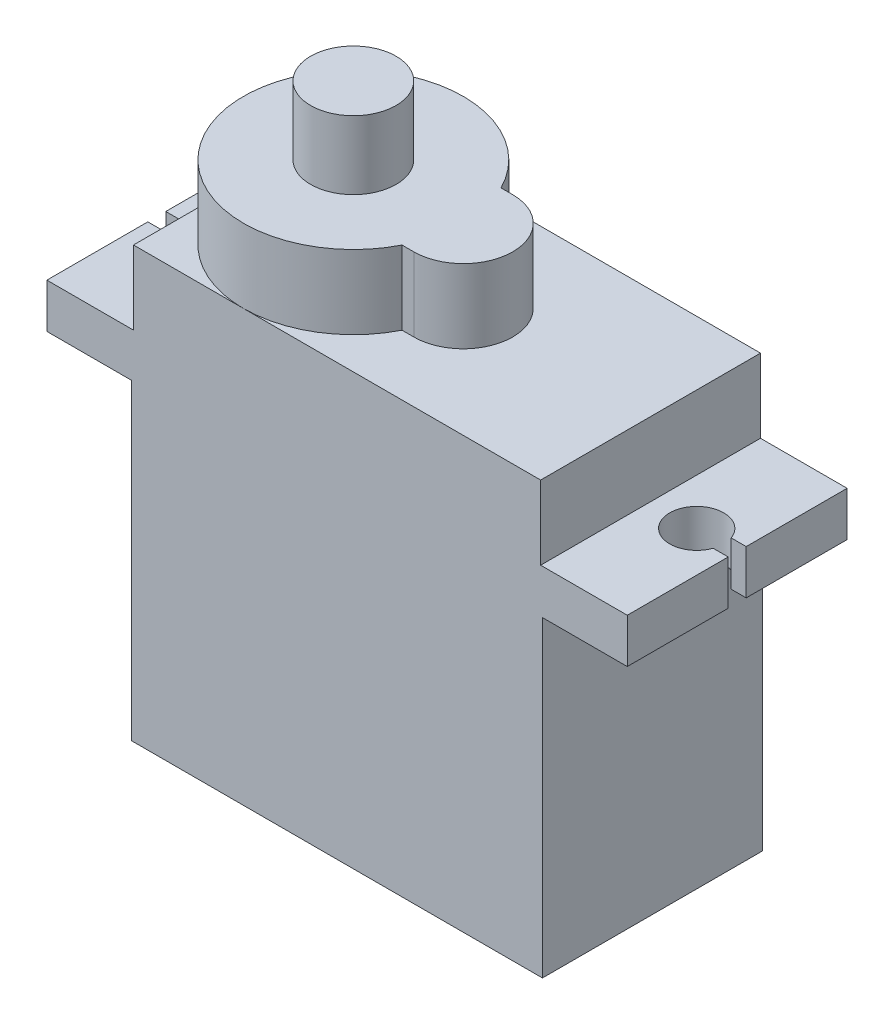
SolidWorks part; units mm, degrees
ref_plane "Front Plane" through (0, 0, 0) normal (0, 0, 1) x (1, 0, 0)
ref_plane "Top Plane" through (0, 0, 0) normal (0, 1, 0) x (1, 0, 0)
ref_plane "Right Plane" through (0, 0, 0) normal (1, 0, 0) x (0, 0, -1)
sketch "Sketch1" plane through (0, 0, 0) normal (0, 1, 0) x (1, 0, 0)
  line L1 (0, 0) -> (22.83, 0)
  line L2 (0, 0) -> (0, 12.22)
  line L3 (0, 12.22) -> (22.83, 12.22)
  line L4 (22.83, 0) -> (22.83, 12.22)
  dimension "D1" = 22.83
  dimension "D2" = 12.22
extrude "Boss-Extrude1" add sketch "Sketch1" along normal blind 17.35
sketch "Sketch2" plane through (0, 17.35, 0) normal (0, 1, 0) x (1, 0, 0)
  line L0 (22.83, 12.22) -> (0, 12.22) construction
  line L1 (-4.715, 0) -> (27.545, 0)
  line L2 (-4.715, 0) -> (-4.715, 12.22) construction
  line L3 (-4.715, 12.22) -> (27.545, 12.22)
  line L5 (0, 0) -> (22.83, 0) construction
  line L6 (11.415, 0) -> (11.415, 12.22) construction
  line L7 (-4.715, 5.61) -> (-3.8792, 5.61)
  line L8 (-2.465, 6.11) -> (-4.715, 6.11) construction
  line L9 (-2.465, 6.11) -> (-0.965, 6.11) construction
  line L10 (-4.715, 6.61) -> (-3.8792, 6.61)
  line L11 (-4.715, 0) -> (-4.715, 5.61)
  line L12 (-4.715, 6.61) -> (-4.715, 12.22)
  line L13 (25.295, 6.11) -> (23.795, 6.11) construction
  line L14 (25.295, 6.11) -> (27.545, 6.11) construction
  line L15 (27.545, 0) -> (27.545, 12.22) construction
  line L16 (27.545, 6.61) -> (27.545, 12.22)
  line L17 (27.545, 0) -> (27.545, 5.61)
  line L18 (27.545, 6.61) -> (26.7092, 6.61)
  line L19 (27.545, 5.61) -> (26.7092, 5.61)
  arc A0 (-3.8792, 5.61) -> (-3.8792, 6.61) centre (-2.465, 6.11) ccw
  arc A1 (26.7092, 5.61) -> (26.7092, 6.61) centre (25.295, 6.11) cw
  point P17 (-1.8734, 6.11)
  point P18 (0, 0)
  dimension "D2" = 1.5
  dimension "D1" = 32.26
  dimension "D3" = 0.5
  dimension "D4" = 3.75
extrude "Boss-Extrude2" add sketch "Sketch2" along normal blind 2.47
sketch "Sketch3" plane through (0, 19.82, 0) normal (0, 1, 0) x (1, 0, 0)
  line L0 (11.415, 0) -> (11.415, 12.22) construction
  line L1 (0.1, 12.22) -> (22.73, 12.22)
  line L2 (0.1, 12.22) -> (0.1, 0)
  line L3 (0.1, 0) -> (22.73, 0)
  line L4 (22.73, 12.22) -> (22.73, 0)
  line L5 (-4.715, 0) -> (27.545, 0) construction
  line L6 (27.545, 12.22) -> (-4.715, 12.22) construction
  point P4 (0, 0)
  dimension "D1" = 22.63
extrude "Boss-Extrude3" add sketch "Sketch3" along normal blind 4.1
sketch "Sketch4" plane through (0, 23.92, 0) normal (0, 1, 0) x (1, 0, 0)
  line L0 (0.1, 12.22) -> (0.1, 0) construction
  line L1 (0.1, 0) -> (22.73, 0) construction
  line L2 (22.73, 12.22) -> (0.1, 12.22) construction
  line L3 (12.32, 3.36) -> (11.6662, 3.36)
  line L4 (12.32, 8.86) -> (11.6662, 8.86)
  arc A0 (11.6662, 8.86) -> (11.6662, 3.36) centre (6.21, 6.11) ccw
  arc A1 (12.32, 3.36) -> (12.32, 8.86) centre (12.32, 6.11) ccw
  dimension "D1" = 5.5
extrude "Boss-Extrude4" add sketch "Sketch4" along normal blind 4.1
sketch "Sketch5" plane through (0, 28.02, 0) normal (0, 1, 0) x (1, 0, 0)
  circle A0 centre (6.21, 6.11) radius 2.375
  arc A2 (11.6662, 8.86) -> (11.6662, 3.36) centre (6.21, 6.11) ccw construction
  point P2 (0, 0)
  dimension "D1" = 4.75
extrude "Boss-Extrude5" add sketch "Sketch5" along normal blind 3.8
